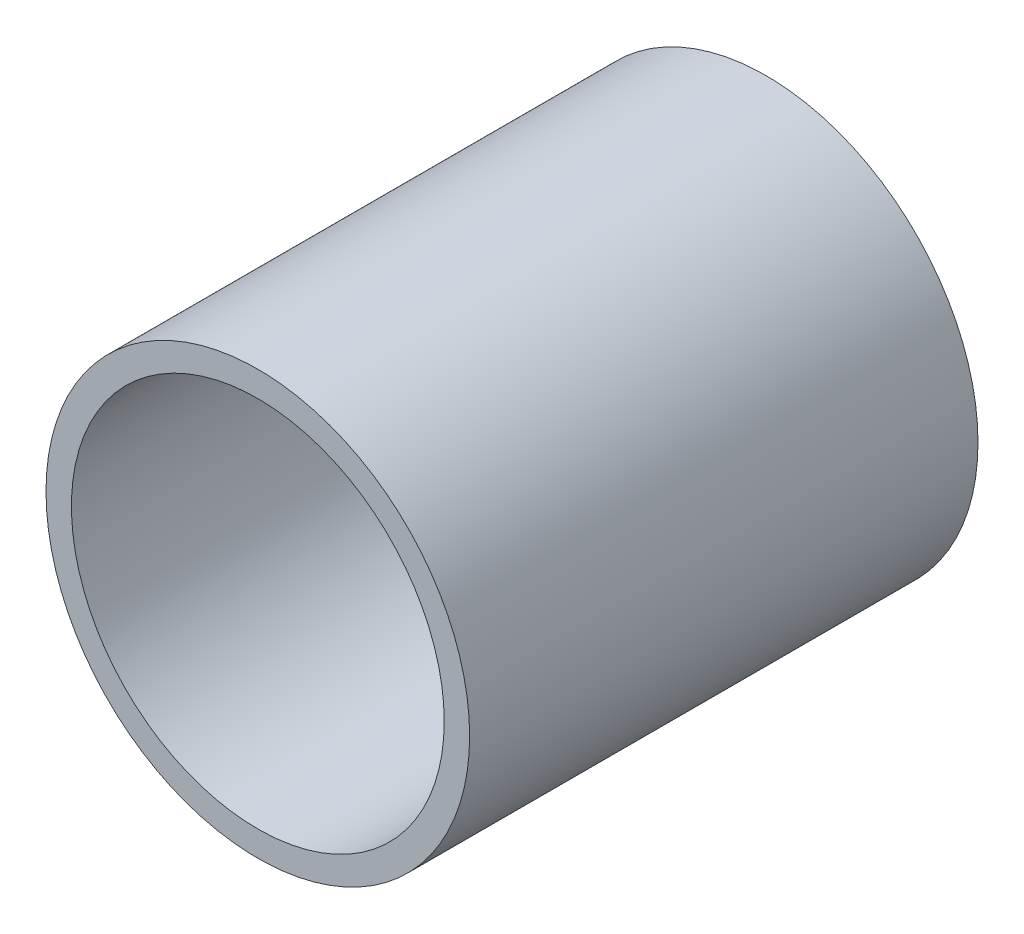
SolidWorks part; units mm, degrees
ref_plane "Front Plane" through (0, 0, 0) normal (0, 0, 1) x (1, 0, 0)
ref_plane "Top Plane" through (0, 0, 0) normal (0, 1, 0) x (1, 0, 0)
ref_plane "Right Plane" through (0, 0, 0) normal (1, 0, 0) x (0, 0, -1)
sketch "Sketch1" plane through (0, 0, 0) normal (0, 0, 1) x (1, 0, 0)
  circle A0 centre (0, 0) radius 2.5
  circle A1 centre (0, 0) radius 2.2
  dimension "D1" = 5
  dimension "D2" = 4.4
extrude "Boss-Extrude1" add sketch "Sketch1" along normal blind 6
other "Freeze***"
